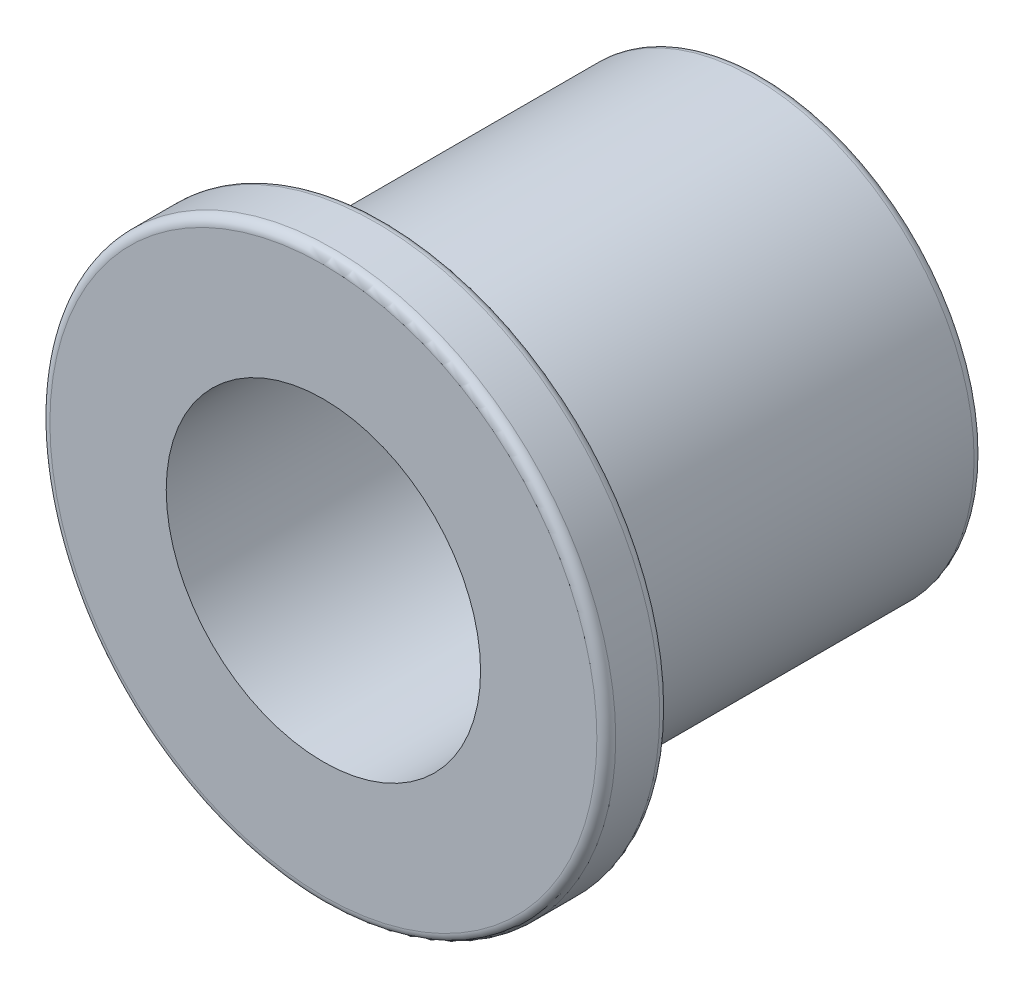
SolidWorks part; units mm, degrees
ref_plane "Front Plane" through (0, 0, 0) normal (0, 0, 1) x (1, 0, 0)
ref_plane "Top Plane" through (0, 0, 0) normal (0, 1, 0) x (1, 0, 0)
ref_plane "Right Plane" through (0, 0, 0) normal (1, 0, 0) x (0, 0, -1)
sketch "Sketch1" plane through (0, 0, 0) normal (0, 0, 1) x (1, 0, 0)
  circle A0 centre (0, 0) radius 7
  circle A1 centre (0, 0) radius 5
  dimension "D1" = 14
  dimension "D2" = 10
extrude "Boss-Extrude1" add sketch "Sketch1" along normal blind 12
sketch "Sketch2" plane through (0, 0, 12) normal (0, 0, 1) x (1, 0, 0)
  circle A0 centre (0, 0) radius 5 construction
  circle A1 centre (0, 0) radius 7
  circle A2 centre (0, 0) radius 7
  circle A3 centre (0, 0) radius 5
  circle A4 centre (0, 0) radius 9
  circle M4 centre (0, 0) radius 7
  circle M5 centre (0, 0) radius 5
  dimension "D2" = 18
  dimension "D1" = 0
extrude "Boss-Extrude2" add sketch "Sketch2" along normal blind 2 contours A4 M4 | M4 M5
fillet "Fillet1" radius 0.3 4 edges at (9, 0, 14) (9, 0, 12) (7, 0, 0) (7, 0, 12)
